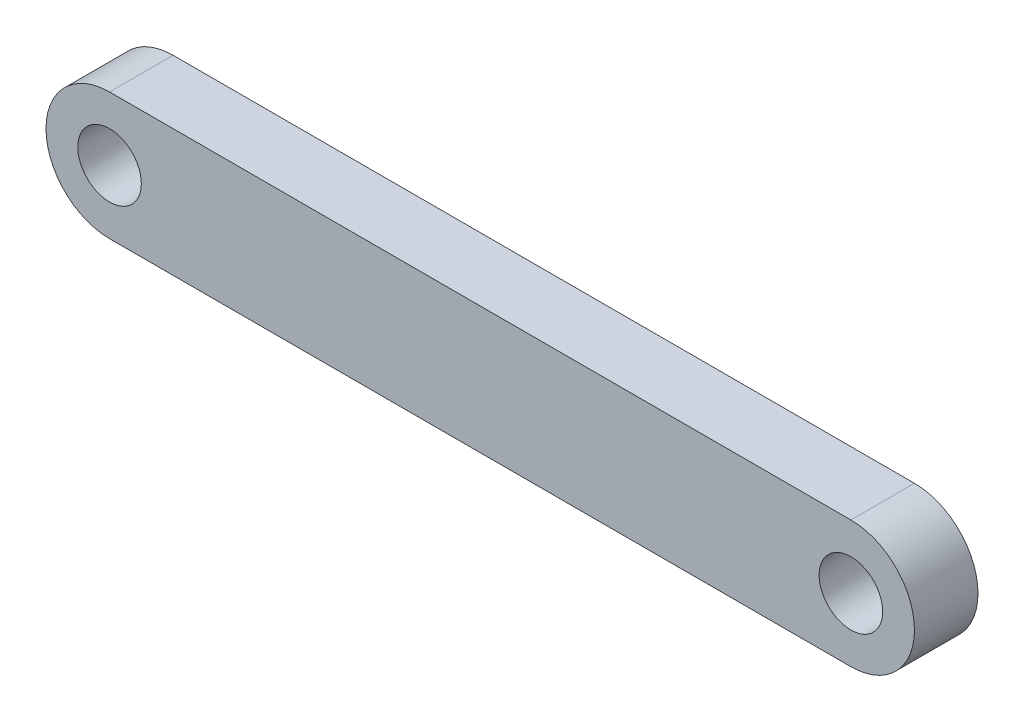
SolidWorks part; units mm, degrees
ref_plane "Front Plane" through (0, 0, 0) normal (0, 0, 1) x (1, 0, 0)
ref_plane "Top Plane" through (0, 0, 0) normal (0, 1, 0) x (1, 0, 0)
ref_plane "Right Plane" through (0, 0, 0) normal (1, 0, 0) x (0, 0, -1)
sketch "Sketch1" plane through (0, 0, 0) normal (0, 0, 1) x (1, 0, 0)
  line L0 (0, 0) -> (-35, 0)
  dimension "D1" = 35
sketch "Sketch2" plane through (0, 0, 0) normal (0, 0, 1) x (1, 0, 0)
  line L0 (-35, 3) -> (0, 3)
  line L1 (-35, -3) -> (0, -3)
  circle A0 centre (-35, 0) radius 1.5
  circle A1 centre (0, 0) radius 1.5
  arc A2 (-35, 3) -> (-35, -3) centre (-35, 0) ccw
  arc A3 (0, -3) -> (0, 3) centre (0, 0) ccw
  dimension "D1" = 3
  dimension "D2" = 6
  dimension "D3" = 3
  dimension "D4" = 6
extrude "Boss-Extrude1" add sketch "Sketch2" along normal blind 3
